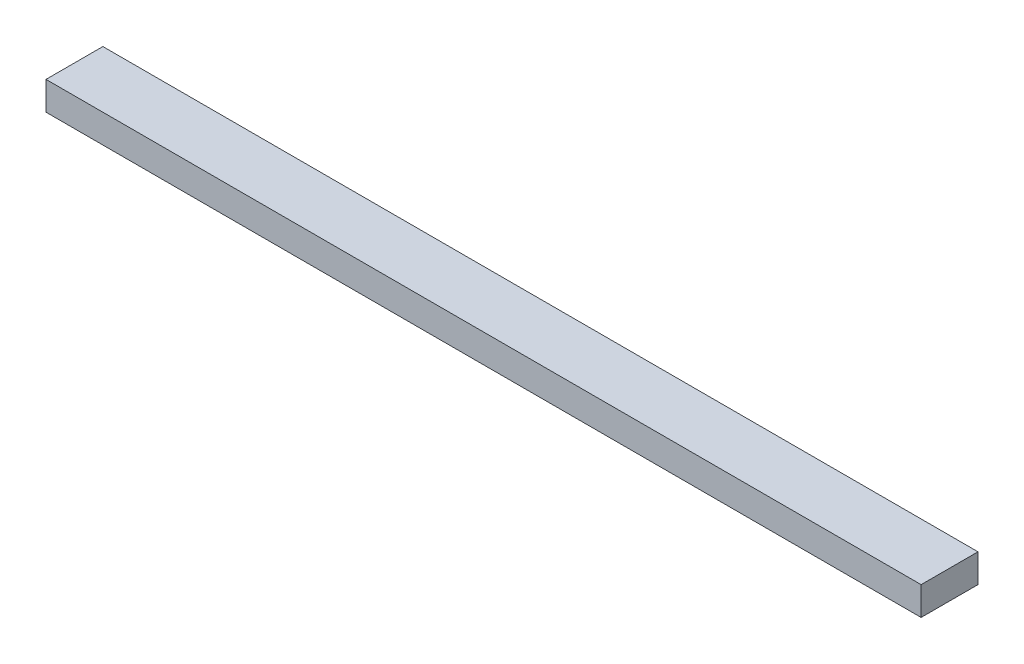
SolidWorks part; units mm, degrees
material "Acrylic (Medium-high impact)"
ref_plane "Front Plane" through (0, 0, 0) normal (0, 0, 1) x (1, 0, 0)
ref_plane "Top Plane" through (0, 0, 0) normal (0, 1, 0) x (1, 0, 0)
ref_plane "Right Plane" through (0, 0, 0) normal (1, 0, 0) x (0, 0, -1)
sketch "Sketch1" plane through (0, 0, 0) normal (0, 1, 0) x (1, 0, 0)
  line L1 (0, 0) -> (97.7, 0)
  line L2 (0, 0) -> (0, 6.35)
  line L3 (0, 6.35) -> (97.7, 6.35)
  line L4 (97.7, 0) -> (97.7, 6.35)
  dimension "D1" = 97.7
  dimension "D2" = 6.35
extrude "Boss-Extrude1" add sketch "Sketch1" along normal blind 3.175
